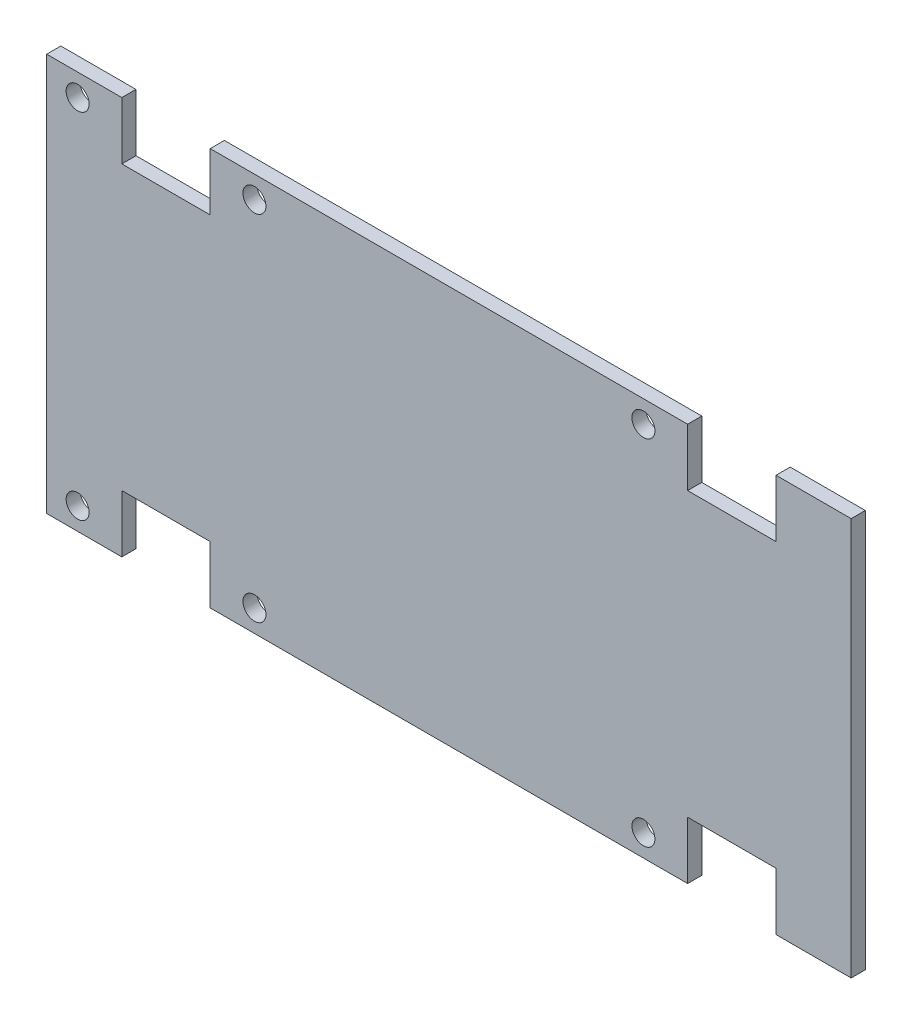
SolidWorks part; units mm, degrees
ref_plane "Спереди" through (0, 0, 0) normal (0, 0, 1) x (1, 0, 0)
ref_plane "Сверху" through (0, 0, 0) normal (0, 1, 0) x (1, 0, 0)
ref_plane "Справа" through (0, 0, 0) normal (1, 0, 0) x (0, 0, -1)
sketch "Эскиз1" plane through (0, 0, 0) normal (0, 0, 1) x (1, 0, 0)
  line L1 (-45.5, 22.5) -> (45.5, 22.5)
  line L2 (-45.5, 22.5) -> (-45.5, -22.5)
  line L3 (-45.5, -22.5) -> (45.5, -22.5)
  line L4 (45.5, 22.5) -> (45.5, -22.5)
  line L5 (-45.5, 22.5) -> (45.5, -22.5) construction
  line L6 (-45.5, -22.5) -> (45.5, 22.5) construction
  point P0 (0, 0)
  dimension "D1" = 91
  dimension "D2" = 45
extrude "Бобышка-Вытянуть1" add sketch "Эскиз1" along normal blind 1.6
sketch "Эскиз2" plane through (0, 0, 0) normal (0, 0, -1) x (-1, 0, 0)
  line L0 (-22, 22.5) -> (-22, -22.5) construction
  line L1 (-45.5, 22.5) -> (45.5, 22.5) construction
  line L2 (45.5, -22.5) -> (-45.5, -22.5) construction
  line L3 (22, 22.5) -> (22, -22.5) construction
  line L4 (42, 22.5) -> (42, -22.5) construction
  line L5 (-45.5, 20) -> (45.5, 20) construction
  line L6 (-45.5, -22.5) -> (-45.5, 22.5) construction
  line L7 (45.5, 22.5) -> (45.5, -22.5) construction
  line L8 (-45.5, -20) -> (45.5, -20) construction
  circle A0 centre (22, 20) radius 1.3
  circle A1 centre (-22, 20) radius 1.3
  circle A2 centre (42, 20) radius 1.3
  circle A3 centre (42, -20) radius 1.3
  circle A4 centre (22, -20) radius 1.3
  circle A5 centre (-22, -20) radius 1.3
  circle A6 centre (-22, -20) radius 2.5 construction
  circle A7 centre (22, 20) radius 2.5 construction
  circle A8 centre (22, -20) radius 2.5 construction
  circle A9 centre (42, 20) radius 2.5 construction
  circle A10 centre (42, -20) radius 3.5 construction
extrude "Вырез-Вытянуть1" cut sketch "Эскиз2" against normal up to surface (1.6 mm away) up to face at (0, 0, 1.6)
sketch "Эскиз5" plane through (0, 0, 0) normal (0, 0, -1) x (-1, 0, 0)
  line L0 (-32, 20.5) -> (-32, -20.5) construction
  line L1 (-32, -20.5) -> (32, -20.5) construction
  line L2 (32, -20.5) -> (32, 20.5) construction
  line L3 (32, 20.5) -> (-32, 20.5) construction
  line L4 (-37, 22.5) -> (-37, 16)
  line L5 (-45.5, 22.5) -> (45.5, 22.5) construction
  line L6 (-37, 16) -> (-27, 16)
  line L7 (-27, 16) -> (-27, 22.5)
  line L8 (27, 22.5) -> (27, 16)
  line L9 (27, 16) -> (37, 16)
  line L10 (37, 16) -> (37, 22.5)
  line L11 (-45.5, 0) -> (45.5, 0) construction
  line L12 (-45.5, -22.5) -> (-45.5, 22.5) construction
  line L13 (45.5, 22.5) -> (45.5, -22.5) construction
  line L14 (37, -16) -> (37, -22.5)
  line L15 (27, -16) -> (37, -16)
  line L16 (27, -22.5) -> (27, -16)
  line L17 (-37, -22.5) -> (-37, -16)
  line L18 (-37, -16) -> (-27, -16)
  line L19 (-27, -16) -> (-27, -22.5)
  line L20 (-37, 22.5) -> (-27, 22.5)
  line L21 (27, 22.5) -> (37, 22.5)
  line L22 (27, -22.5) -> (37, -22.5)
  line L23 (-37, -22.5) -> (-27, -22.5)
  dimension "D1" = 10
  dimension "D2" = 5
  dimension "D3" = 6.5
  dimension "D4" = 5
extrude "Вырез-Вытянуть2" cut sketch "Эскиз5" against normal up to surface (1.6 mm away) up to face at (23.3, 20, 1.6)
